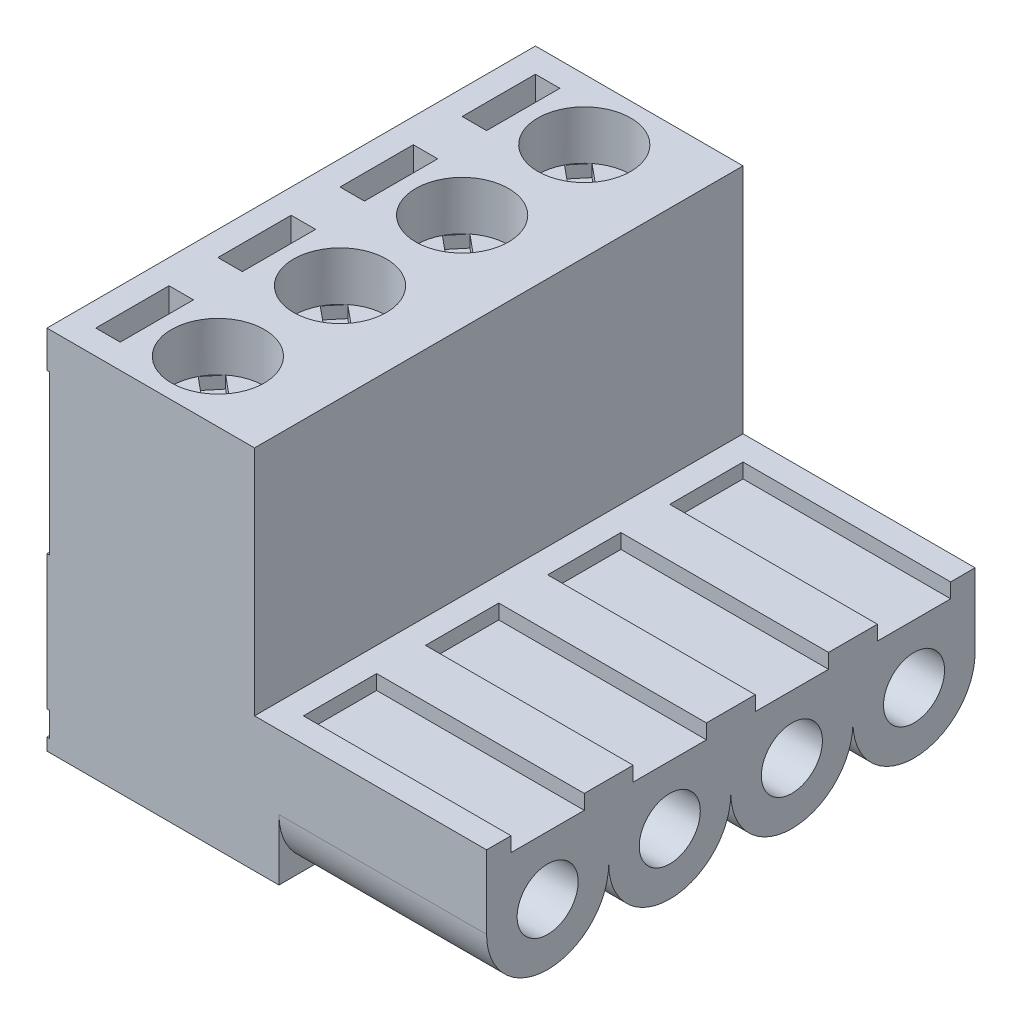
SolidWorks part; units mm, degrees
ref_plane "Спереди" through (0, 0, 0) normal (0, 0, 1) x (1, 0, 0)
ref_plane "Сверху" through (0, 0, 0) normal (0, 1, 0) x (1, 0, 0)
ref_plane "Справа" through (0, 0, 0) normal (1, 0, 0) x (0, 0, -1)
sketch "Эскиз1" plane through (0, 0, 0) normal (0, 0, 1) x (1, 0, 0)
  line L1 (0, 0) -> (9.5, 0)
  line L2 (0, 0) -> (0, 15)
  line L3 (0, 15) -> (8.5, 15)
  line L4 (9.5, 0) -> (9.5, 5.5)
  line L6 (8.5, 15) -> (8.5, 5.5)
  line L7 (8.5, 5.5) -> (9.5, 5.5)
  dimension "D1" = 15
  dimension "D2" = 1
  dimension "D3" = 8.5
  dimension "D4" = 5.5
extrude "Вытянуть1" add sketch "Эскиз1" along normal blind 25
sketch "Эскиз2" plane through (9.5, 0, 0) normal (1, 0, 0) x (0, 0, -1)
  line L0 (-25, 0) -> (0, 0) construction
  line L1 (-25, 5.5) -> (-24, 5.5)
  line L2 (-25, 5.5) -> (0, 5.5) construction
  line L3 (-24, 5.5) -> (-24, 4.9)
  line L4 (-24, 4.9) -> (-21, 4.9)
  line L5 (-21, 4.9) -> (-21, 5.5)
  line L6 (-21, 5.5) -> (-20, 5.5)
  line L7 (-20, 5.5) -> (-20, 2.5)
  line L8 (-25, 5.5) -> (-25, 2.5)
  line L9 (-25, 0) -> (-25, 5.5) construction
  circle A0 centre (-22.5, 2.5) radius 1.25
  arc A1 (-25, 2.5) -> (-20, 2.5) centre (-22.5, 2.5) ccw
  dimension "D1" = 5
  dimension "D5" = 2.5
  dimension "D2" = 3
  dimension "D3" = 1
  dimension "D4" = 5
  dimension "D6" = 0.6
extrude "Вытянуть2" add sketch "Эскиз2" along normal blind 8.5
pattern_linear "Линейный массив1" count 5 spacing 5 along (0, 0, -1) of "Вытянуть2"
sketch "Эскиз3" plane through (0, 0, 0) normal (-1, 0, 0) x (0, 0, 1)
  line L0 (0, 15) -> (0, 0) construction
  line L1 (1, 5.8) -> (4, 5.8)
  line L2 (1, 5.8) -> (1, 2.5)
  line L3 (1, 2.5) -> (4, 2.5)
  line L4 (4, 5.8) -> (4, 2.5)
  line L5 (25, 0) -> (0, 0) construction
  dimension "D1" = 3
  dimension "D2" = 3.3
  dimension "D3" = 1
  dimension "D4" = 2.5
extrude "Вырез-Вытянуть1" cut sketch "Эскиз3" against normal blind 3
pattern_linear "Линейный массив2" count 5 spacing 5 along (0, 0, 1) of "Вырез-Вытянуть1"
sketch "Эскиз4" plane through (0, 0, 0) normal (-1, 0, 0) x (0, 0, 1)
  line L0 (0, 15) -> (0, 0) construction
  line L1 (0, 13.5) -> (25, 13.5)
  line L2 (0, 13.5) -> (0, 12.5)
  line L3 (0, 12.5) -> (4.5, 12.5)
  line L4 (25, 13.5) -> (25, 12.5)
  line L5 (25, 15) -> (25, 0) construction
  line L6 (5.5, 12.5) -> (9.5, 12.5)
  line L7 (10.5, 12.5) -> (14.5, 12.5)
  line L8 (4.5, 12.5) -> (4.5, 7)
  line L9 (4.5, 7) -> (5.5, 7)
  line L10 (5.5, 12.5) -> (5.5, 7)
  line L11 (15.5, 12.5) -> (19.5, 12.5)
  line L12 (9.5, 12.5) -> (9.5, 7)
  line L13 (9.5, 7) -> (10.5, 7)
  line L14 (10.5, 12.5) -> (10.5, 7)
  line L15 (20.5, 12.5) -> (24.5, 12.5)
  line L16 (14.5, 12.5) -> (14.5, 7)
  line L17 (14.5, 7) -> (15.5, 7)
  line L18 (15.5, 12.5) -> (15.5, 7)
  line L19 (25.5, 12.5) -> (25, 12.5)
  line L20 (19.5, 12.5) -> (19.5, 7)
  line L21 (19.5, 7) -> (20.5, 7)
  line L22 (20.5, 12.5) -> (20.5, 7)
  line L23 (25, 15) -> (0, 15) construction
  line L24 (24.5, 12.5) -> (24.5, 7)
  line L25 (24.5, 7) -> (25.5, 7)
  line L26 (25.5, 12.5) -> (25.5, 7)
  dimension "D1" = 1
  dimension "D2" = 1
  dimension "D3" = 4.5
  dimension "D4" = 8
  dimension "D5" = 1.5
  dimension "D6" = 5
  dimension "D7" = 5
  dimension "D8" = 5
  dimension "D9" = 5
extrude "Вырез-Вытянуть2" cut sketch "Эскиз4" against normal blind 0.1
sketch "Эскиз5" plane through (0, 0, 0) normal (-1, 0, 0) x (0, 0, 1)
  line L0 (0, 12.5) -> (0, 0) construction
  line L1 (0, 1.5) -> (25, 1.5)
  line L2 (0, 1.5) -> (0, 0.5)
  line L3 (0, 0.5) -> (25, 0.5)
  line L4 (25, 1.5) -> (25, 0.5)
  line L5 (25, 7) -> (25, 0) construction
  line L6 (25, 0) -> (0, 0) construction
  dimension "D1" = 1
  dimension "D2" = 0.5
extrude "Вырез-Вытянуть3" cut sketch "Эскиз5" against normal blind 0.1
sketch "Эскиз6" plane through (0, 15, 0) normal (0, 1, 0) x (-1, 0, 0)
  line L1 (-8.5, 0) -> (0, 0) construction
  line L2 (0, 25) -> (0, 0) construction
  circle A0 centre (-4.5, 2.5) radius 1.9
  dimension "D1" = 3.8
  dimension "D2" = 2.5
  dimension "D3" = 4.5
extrude "Вырез-Вытянуть4" cut sketch "Эскиз6" against normal blind 2
pattern_linear "Линейный массив3" count 5 spacing 5 along (0, 0, 1) of "Вырез-Вытянуть4"
sketch "Эскиз7" plane through (0, 15, 0) normal (0, 1, 0) x (-1, 0, 0)
  line L0 (-8.5, 0) -> (0, 0) construction
  line L1 (-2, 1) -> (-1, 1)
  line L2 (-2, 1) -> (-2, 4)
  line L3 (-2, 4) -> (-1, 4)
  line L4 (-1, 1) -> (-1, 4)
  dimension "D1" = 3
  dimension "D2" = 1
  dimension "D3" = 1
  dimension "D4" = 1
extrude "Вырез-Вытянуть5" cut sketch "Эскиз7" against normal blind 2
pattern_linear "Линейный массив4" count 5 spacing 5 along (0, 0, 1) of "Вырез-Вытянуть5"
sketch "Эскиз8" plane through (0, 13, 0) normal (0, 1, 0) x (-1, 0, 0)
  line L0 (-6.1854, 3.3771) -> (-3.325, 1.0069)
  line L1 (-3.325, 1.0069) -> (-2.8146, 1.6229)
  line L2 (-2.8146, 1.6229) -> (-5.675, 3.9931)
  line L3 (-5.675, 3.9931) -> (-6.1854, 3.3771)
  circle A0 centre (-4.5, 2.5) radius 1.9 construction
  dimension "D1" = 0.8
extrude "Вырез-Вытянуть6" cut sketch "Эскиз8" against normal blind 0.5
pattern_linear "Линейный массив5" count 5 spacing 5 along (0, 0, 1) of "Вырез-Вытянуть6"
sketch "Эскиз9" plane through (0, 0, 25) normal (0, 0, 1) x (1, 0, 0)
  line L1 (0, 15) -> (18, 15)
  line L2 (0, 15) -> (0, 0)
  line L3 (0, 0) -> (18, 0)
  line L4 (18, 15) -> (18, 0)
extrude "Вырез-Вытянуть7" cut sketch "Эскиз9" against normal blind 5
